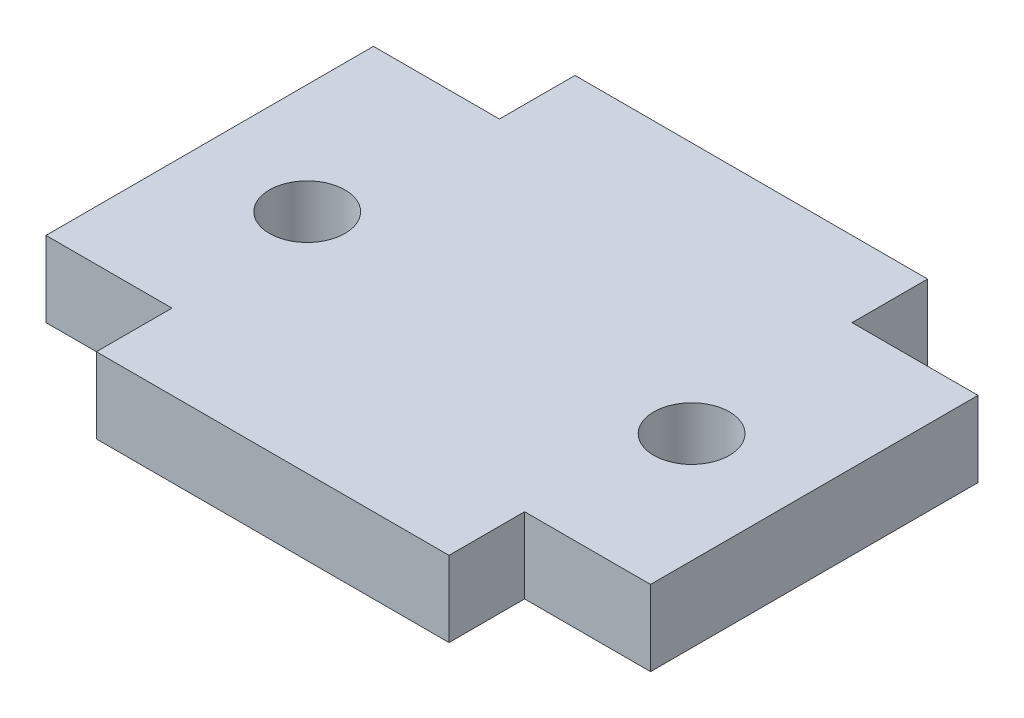
SolidWorks part; units mm, degrees
ref_plane "Alzado" through (0, 0, 0) normal (0, 0, 1) x (1, 0, 0)
ref_plane "Planta" through (0, 0, 0) normal (0, 1, 0) x (1, 0, 0)
ref_plane "Vista lateral" through (0, 0, 0) normal (1, 0, 0) x (0, 0, -1)
sketch "Croquis1" plane through (0, 0, 0) normal (0, 1, 0) x (1, 0, 0)
  line L0 (0, 0) -> (0, 13)
  line L1 (0, 13) -> (5, 13)
  line L2 (24, 13) -> (24, 0)
  line L3 (24, 0) -> (19, 0)
  line L4 (5, 0) -> (0, 0)
  line L5 (5, 16) -> (19, 16)
  line L6 (19, 16) -> (19, 13)
  line L7 (5, 16) -> (5, 13)
  line L8 (12, 16) -> (12, -3) construction
  line L9 (5, -3) -> (5, 0)
  line L10 (19, -3) -> (19, 0)
  line L11 (5, -3) -> (19, -3)
  line L12 (0, 6) -> (20, 6) construction
  line L13 (19, 13) -> (24, 13)
  circle A0 centre (4.37, 6) radius 1.5
  circle A1 centre (19.63, 6) radius 1.5
  dimension "D7" = 3
  dimension "D11" = 5
  dimension "D1" = 13
  dimension "D2" = 24
  dimension "D3" = 5
  dimension "D4" = 3
  dimension "D5" = 7
  dimension "D6" = 19
  dimension "D8" = 7.63
  dimension "D9" = 3
  dimension "D10" = 3
  dimension "D12" = 5
extrude "Saliente-Extruir1" add sketch "Croquis1" along normal blind 3
